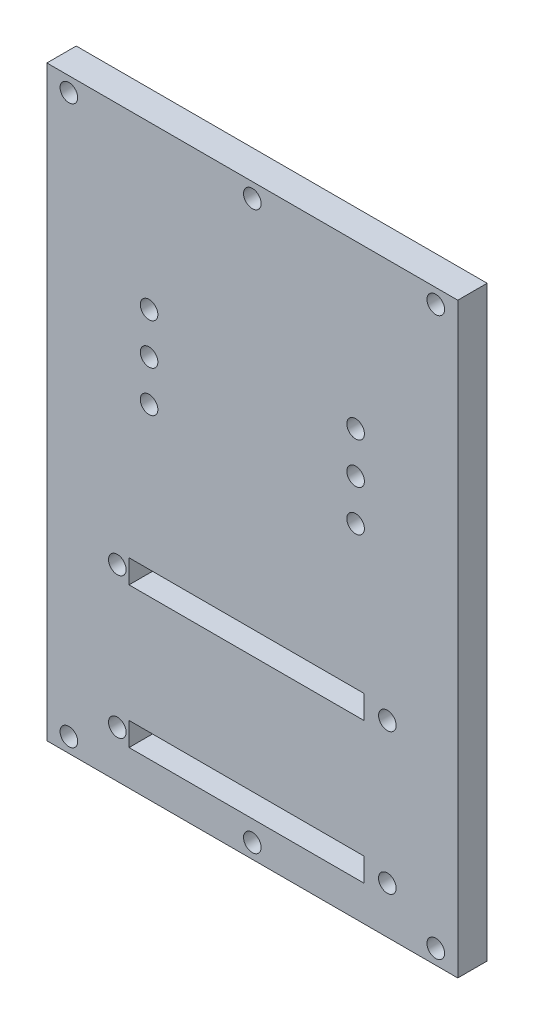
SolidWorks part; units mm, degrees
ref_plane "Front Plane" through (0, 0, 0) normal (0, 0, 1) x (1, 0, 0)
ref_plane "Top Plane" through (0, 0, 0) normal (0, 1, 0) x (1, 0, 0)
ref_plane "Right Plane" through (0, 0, 0) normal (1, 0, 0) x (0, 0, -1)
sketch "Sketch1" plane through (0, 0, 0) normal (0, 0, 1) x (1, 0, 0)
  line L1 (-35, -50) -> (35, -50)
  line L2 (-35, -50) -> (-35, 50)
  line L3 (-35, 50) -> (35, 50)
  line L4 (35, -50) -> (35, 50)
  line L5 (-35, -50) -> (35, 50) construction
  line L6 (-35, 50) -> (35, -50) construction
  point P0 (0, 0)
  dimension "D1" = 70
  dimension "D2" = 100
extrude "Boss-Extrude1" add sketch "Sketch1" along normal mid plane 5
sketch "Sketch2" plane through (0, 0, 2.5) normal (0, 0, 1) x (1, 0, 0)
  line L0 (0, 0) -> (0, 47.5)
  line L1 (0, 47.5) -> (-31.25, 47.5)
  circle A0 centre (0, 47.5) radius 1.5
  circle A1 centre (-31.25, 47.5) radius 1.5
  circle A2 centre (31.25, 47.5) radius 1.5
  dimension "D2" = 3
  dimension "D4" = 3
  dimension "D1" = 47.5
  dimension "D3" = 31.25
extrude "Cut-Extrude1" cut sketch "Sketch2" against normal blind 11 contours A2 | A1 | A0
mirror "Mirror1" about plane through (0, 0, 0) normal (0, 1, 0) of "Cut-Extrude1"
sketch "Sketch3" plane through (0, 0, 2.5) normal (0, 0, 1) x (1, 0, 0)
  line L0 (-35, 50) -> (-35, -10)
  line L1 (-35, 50) -> (-35, -50) construction
  line L2 (-25, -16) -> (-23, -16)
  line L3 (-23, -16) -> (-23, -18)
  line L5 (0, -16) -> (0, -44)
  line L7 (-25, -30) -> (25, -30)
  line L8 (0, -10) -> (0, -30)
  line L9 (-25, -16) -> (-21, -16)
  line L10 (-21, -40) -> (19, -40)
  line L15 (-21, -16) -> (19, -16)
  line L16 (-21, -16) -> (-21, -20)
  line L21 (-25, -16) -> (25, -16)
  line L22 (-25, -16) -> (-25, -44)
  line L23 (-25, -44) -> (25, -44)
  line L24 (25, -16) -> (25, -44)
  line L25 (-25, -16) -> (25, -44) construction
  line L26 (-25, -44) -> (25, -16) construction
  line L27 (-33.595, 45.3213) -> (-1.595, 45.3213)
  line L28 (-33.595, 45.3213) -> (-33.595, -14.6787)
  line L29 (-33.595, -14.6787) -> (-1.595, -14.6787)
  line L30 (-1.595, 45.3213) -> (-1.595, -14.6787)
  line L31 (-33.595, 45.3213) -> (-1.595, -14.6787) construction
  line L32 (-33.595, -14.6787) -> (-1.595, 45.3213) construction
  line L33 (-21, -20) -> (19, -20)
  line L34 (19, -16) -> (19, -20)
  line L35 (19, -44) -> (19, -40)
  line L36 (-21, -44) -> (19, -44)
  line L37 (-21, -44) -> (-21, -40)
  circle A8 centre (-17.595, 15.3213) radius 1.5
  circle A9 centre (-17.595, 22.3213) radius 1.5
  circle A10 centre (-17.595, 15.3213) radius 1.5
  circle A11 centre (-17.595, 8.3213) radius 1.5
  circle A13 centre (17.595, 8.3213) radius 1.5
  circle A14 centre (17.595, 15.3213) radius 1.5
  circle A15 centre (17.595, 22.3213) radius 1.5
  circle A16 centre (-23, -18) radius 1.5
  circle A17 centre (23, -18) radius 1.5
  circle A18 centre (23, -42) radius 1.5
  circle A19 centre (-23, -42) radius 1.5
  dimension "D3" = 20
  dimension "D6" = 2
  dimension "D2" = 3
  dimension "D10" = 3
  dimension "D1" = 60
  dimension "D9" = 2
  dimension "D4" = 32
  dimension "D5" = 60
  dimension "D8" = 2
  dimension "D11" = 4
  dimension "D12" = 40
  dimension "D13" = 4
  dimension "D14" = 28
  dimension "D15" = 50
  dimension "D7" = 2
extrude "Cut-Extrude2" cut sketch "Sketch3" against normal blind 10 contours A16 | A13 | A14 | A15 | A9 | A8 | A19 | A18 | A17 | A11 | L16 L15 L34 L33 | L10 L35 L36 L37
